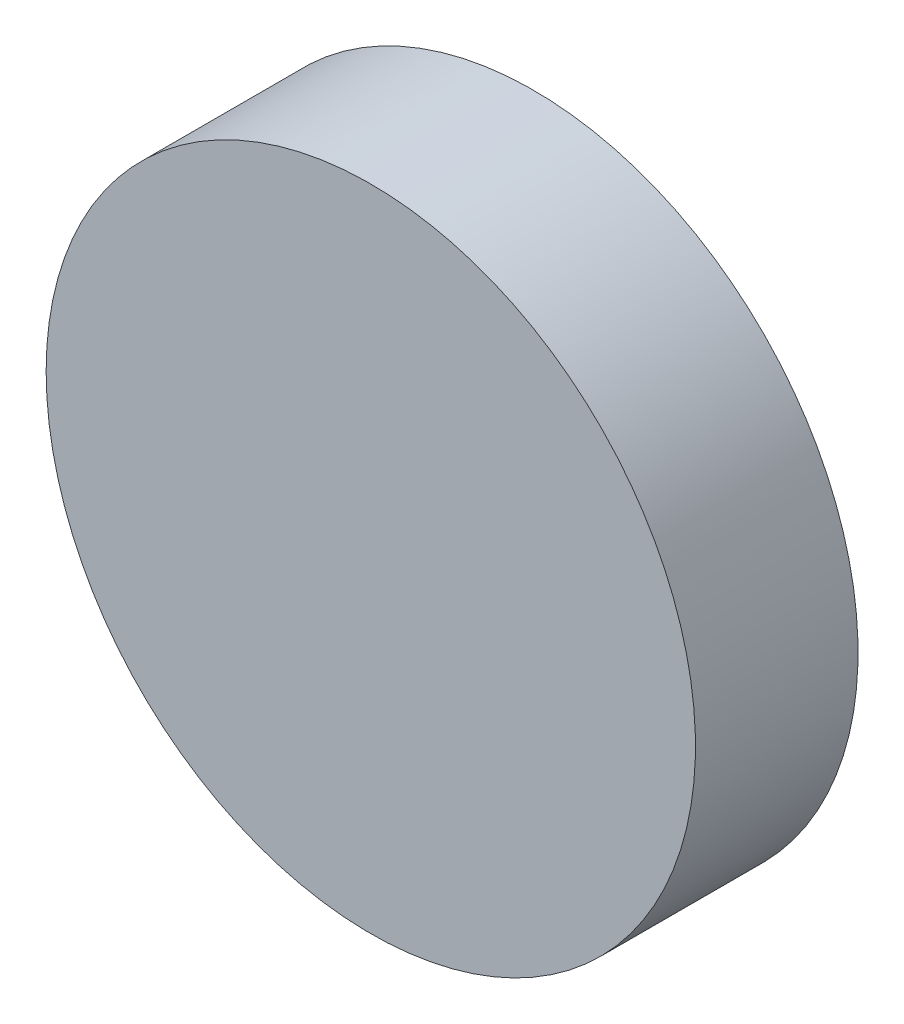
SolidWorks part; units mm, degrees
material "1060 Alloy"
ref_plane "Front Plane" through (0, 0, 0) normal (0, 0, 1) x (1, 0, 0)
ref_plane "Top Plane" through (0, 0, 0) normal (0, 1, 0) x (1, 0, 0)
ref_plane "Right Plane" through (0, 0, 0) normal (1, 0, 0) x (0, 0, -1)
sketch "Sketch2" plane through (0, 0, 0) normal (0, 0, 1) x (1, 0, 0)
  circle A0 centre (0, 0) radius 3.175
  dimension "D1" = 6.35
extrude "Boss-Extrude1" add sketch "Sketch2" along normal blind 1.59
